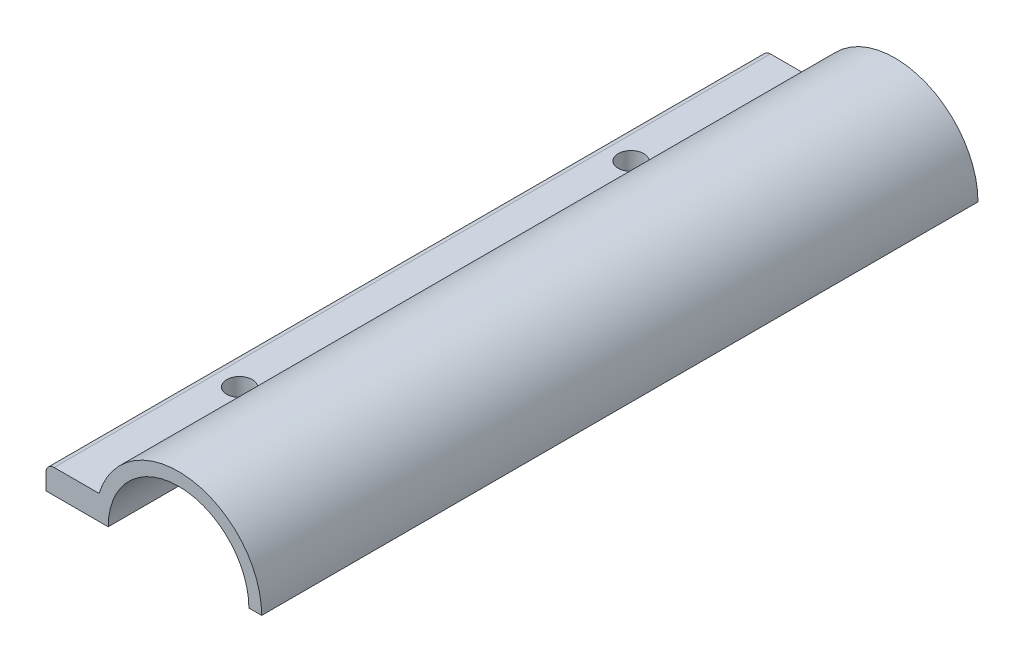
SolidWorks part; units mm, degrees
material "ABS"
ref_plane "X-Y Datum" through (0, 0, 0) normal (0, 0, 1) x (1, 0, 0)
ref_plane "X-Z Datum" through (0, 0, 0) normal (0, 1, 0) x (1, 0, 0)
ref_plane "Y-Z Datum" through (0, 0, 0) normal (1, 0, 0) x (0, 0, -1)
sketch "Sketch1" plane through (0, 0, 0) normal (0, 0, 1) x (1, 0, 0)
  line L0 (-13, 0) -> (-20.7245, 0)
  line L1 (-20.7245, 0) -> (-20.7245, -13)
  line L2 (-20.7245, -13) -> (0, -13)
  line L3 (-13, 0) -> (13, 0)
  line L4 (0, 13) -> (-20.7245, 13)
  line L5 (-20.7245, 13) -> (-20.7245, 0)
  line L6 (-20.7245, 3.81) -> (-12.4292, 3.81)
  circle A0 centre (0, 0) radius 13
  circle A1 centre (0, 0) radius 11
  dimension "D3" = 2
  dimension "D2" = 22
  dimension "D1" = 7.7245
  dimension "D4" = 3.81
extrude "Boss-Extrude1" add sketch "Sketch1" along normal blind 112 contours A1 L3 A0 | A0 L6 L5 L0
sketch "Sketch3" plane through (0, 3.81, 0) normal (0, 1, 0) x (1, 0, 0)
  circle A0 centre (-15.8622, -25.4) radius 2 construction
  circle A1 centre (-15.8622, -86.6) radius 2 construction
  circle A2 centre (-15.8622, -25.4) radius 2
  circle A3 centre (-15.8622, -86.6) radius 2
extrude "Cut-Extrude2" cut sketch "Sketch3" against normal through all
fillet "Fillet1" radius 1.27 1 edges at (-20.7245, 3.81, 56)
